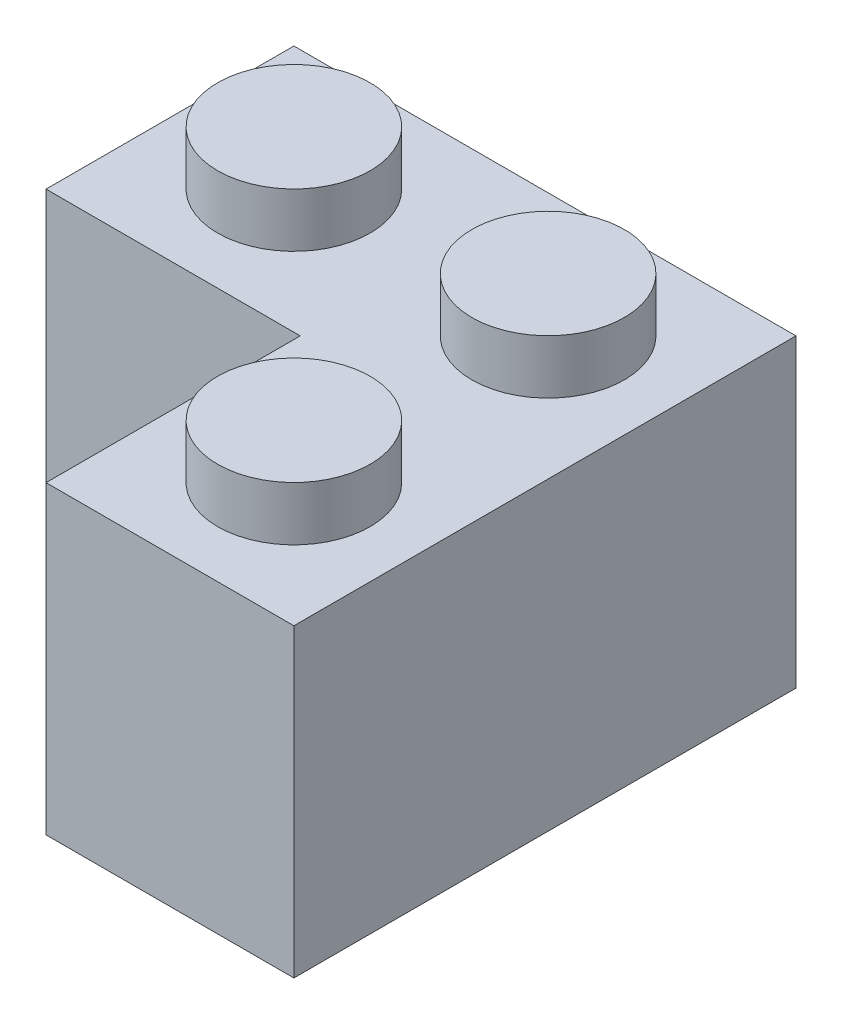
SolidWorks part; units mm, degrees
ref_plane "Спереди" through (0, 0, 0) normal (0, 0, 1) x (1, 0, 0)
ref_plane "Сверху" through (0, 0, 0) normal (0, 1, 0) x (1, 0, 0)
ref_plane "Справа" through (0, 0, 0) normal (1, 0, 0) x (0, 0, -1)
sketch "Эскиз2" plane through (0, 0, 0) normal (0, 1, 0) x (1, 0, 0)
  line L1 (7.9, -7.9) -> (-7.9, -7.9)
  line L2 (7.9, -7.9) -> (7.9, 7.9)
  line L3 (7.9, 7.9) -> (-7.9, 7.9)
  line L4 (-7.9, -7.9) -> (-7.9, 7.9)
  line L5 (7.9, -7.9) -> (-7.9, 7.9) construction
  line L6 (7.9, 7.9) -> (-7.9, -7.9) construction
  point P0 (0, 0)
  dimension "D1" = 15.8
  dimension "D2" = 15.8
extrude "Бобышка-Вытянуть1" add sketch "Эскиз2" along normal blind 9.6
sketch "Эскиз3" plane through (0, 9.6, 0) normal (0, 1, 0) x (1, 0, 0)
  line L2 (-7.9, -7.9) -> (0.1, -7.9)
  line L3 (-7.9, -7.9) -> (-7.9, 0.1)
  line L4 (-7.9, 0.1) -> (0.1, 0.1)
  line L5 (0.1, -7.9) -> (0.1, 0.1)
  dimension "D2" = 8
  dimension "D3" = 8
extrude "Вырез-Вытянуть1" cut sketch "Эскиз3" against normal blind 9.6 contours L3 L2 L5 L4
sketch "Эскиз4" plane through (0, 9.6, 0) normal (0, 1, 0) x (1, 0, 0)
  line L0 (-7.9, 7.9) -> (-7.9, 0.1) construction
  line L1 (-7.9, 0.1) -> (0.1, 0.1) construction
  circle A0 centre (-4, 4) radius 2.4
  circle A1 centre (4, 4) radius 2.4
  circle A2 centre (4, -4) radius 2.4
  dimension "D1" = 3.9
  dimension "D2" = 3.9
  dimension "D3" = 2
  dimension "D4" = 2
extrude "Бобышка-Вытянуть2" add sketch "Эскиз4" along normal blind 1.7
sketch "Эскиз5" plane through (0, 0, 0) normal (0, -1, 0) x (1, 0, 0)
  line L0 (-7.9, -7.9) -> (-7.9, -0.1) construction
  line L1 (7.9, -7.9) -> (-7.9, -7.9) construction
  circle A0 centre (-4, -4) radius 2.5
  circle A1 centre (4, -4) radius 2.5
  circle A2 centre (4, 4) radius 2.5
  dimension "D1" = 3.9
  dimension "D4" = 2
  dimension "D2" = 3.9
  dimension "D3" = 2
extrude "Вырез-Вытянуть2" cut sketch "Эскиз5" against normal blind 1.8
